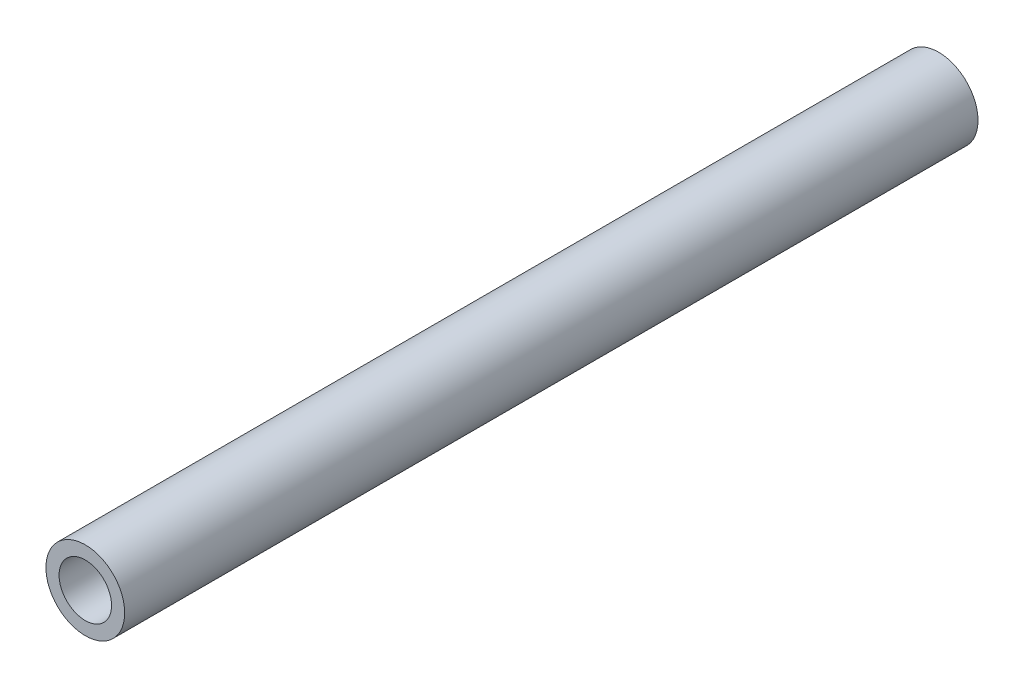
SolidWorks part; units mm, degrees
material "AISI 4140 Steel, quenched & tempered"
ref_plane "Front Plane" through (0, 0, 0) normal (1, 0, 0) x (0, 1, 0)
ref_plane "Top Plane" through (0, 0, 0) normal (0, 0, 1) x (0, 1, 0)
ref_plane "Right Plane" through (0, 0, 0) normal (0, 1, 0) x (-1, 0, 0)
sketch "Sketch1" plane through (0, 0, 0) normal (0, 0, 1) x (0, 1, 0)
  circle A0 centre (0, 0) radius 15
  circle A1 centre (0, 0) radius 10
  dimension "D1" = 30
  dimension "D2" = 20
extrude "Boss-Extrude1" add sketch "Sketch1" along normal mid plane 325
